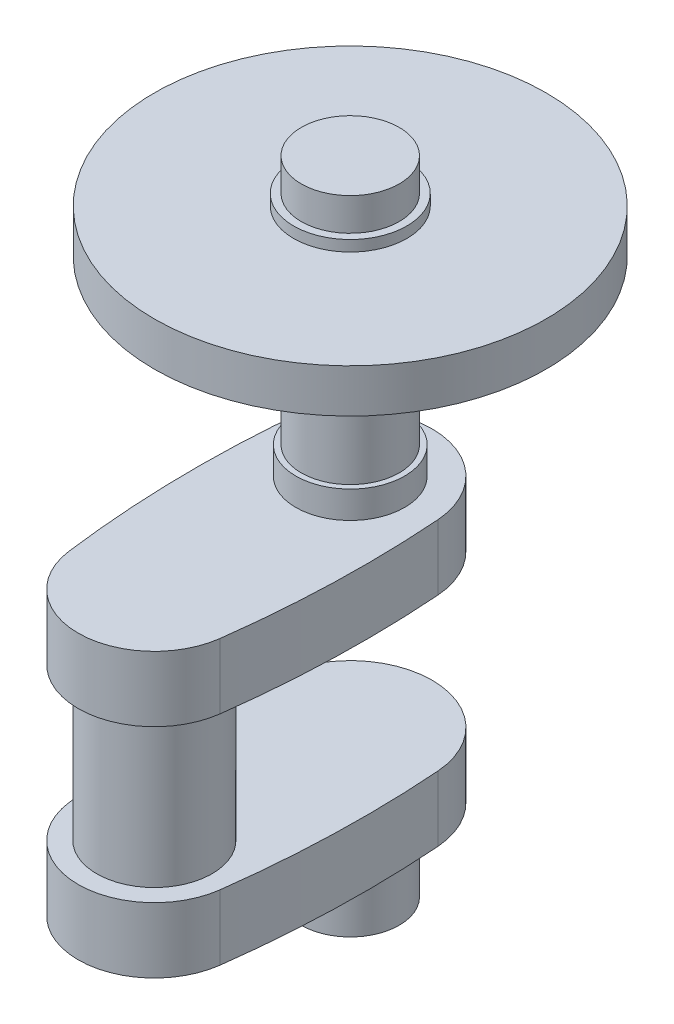
SolidWorks part; units mm, degrees
ref_plane "Front Plane" through (0, 0, 0) normal (0, 0, 1) x (1, 0, 0)
ref_plane "Top Plane" through (0, 0, 0) normal (0, 1, 0) x (1, 0, 0)
ref_plane "Right Plane" through (0, 0, 0) normal (1, 0, 0) x (0, 0, -1)
sketch "Sketch1" plane through (0, 0, 0) normal (0, 1, 0) x (1, 0, 0)
  circle A0 centre (0, 0) radius 22.5
  dimension "D1" = 45
extrude "Boss-Extrude1" add sketch "Sketch1" along normal blind 25
sketch "Sketch2" plane through (0, 0, 0) normal (0, 1, 0) x (1, 0, 0)
  circle A0 centre (0, 0) radius 25
  dimension "D1" = 50
extrude "Boss-Extrude2" add sketch "Sketch2" against normal blind 12.5
sketch "Sketch3" plane through (0, -12.5, 0) normal (0, -1, 0) x (1, 0, 0)
  arc A0 (-37.5, -2.7404) -> (37.5, -2.7404) centre (0, 0) ccw
  arc A1 (34.7027, 94.5523) -> (-34.7027, 94.5523) centre (0, 90) ccw
  arc A3 (34.7027, 94.5523) -> (37.5, -2.7404) centre (-440.617, 32.1996) cw
  arc A4 (-34.7027, 94.5523) -> (-37.5, -2.7404) centre (440.617, 32.1996) ccw
  dimension "D2" = 37.6
  dimension "D3" = 90
  dimension "D4" = 70
  dimension "D1" = 75
extrude "Boss-Extrude3" add sketch "Sketch3" along normal blind 30
sketch "Sketch4" plane through (0, -42.5, 0) normal (0, -1, 0) x (1, 0, 0)
  circle A0 centre (0, 90) radius 26.5
  dimension "D1" = 53
  dimension "D2" = 90
extrude "Boss-Extrude4" add sketch "Sketch4" along normal blind 35
mirror "Mirror1" about plane through (0, -77.5, 90) normal (0, -1, 0) of bodies 104
sketch "Sketch5" plane through (0, 25, 0) normal (0, 1, 0) x (1, 0, 0)
  circle A0 centre (0, 0) radius 22.5
extrude "Boss-Extrude5" add sketch "Sketch5" along normal blind 50
sketch "Sketch6" plane through (0, 75, 0) normal (0, 1, 0) x (1, 0, 0)
  circle A0 centre (0, 0) radius 90
extrude "Boss-Extrude6" add sketch "Sketch6" along normal blind 20
sketch "Sketch7" plane through (0, 95, 0) normal (0, 1, 0) x (1, 0, 0)
  circle A0 centre (0, 0) radius 22.5
extrude "Boss-Extrude7" add sketch "Sketch7" along normal blind 20
sketch "Sketch8" plane through (0, 75, 0) normal (0, -1, 0) x (1, 0, 0)
  circle A0 centre (0, 0) radius 26
extrude "Boss-Extrude8" add sketch "Sketch8" along normal blind 5
sketch "Sketch9" plane through (0, 95, 0) normal (0, 1, 0) x (1, 0, 0)
  circle A0 centre (0, 0) radius 26
extrude "Boss-Extrude9" add sketch "Sketch9" along normal blind 5
